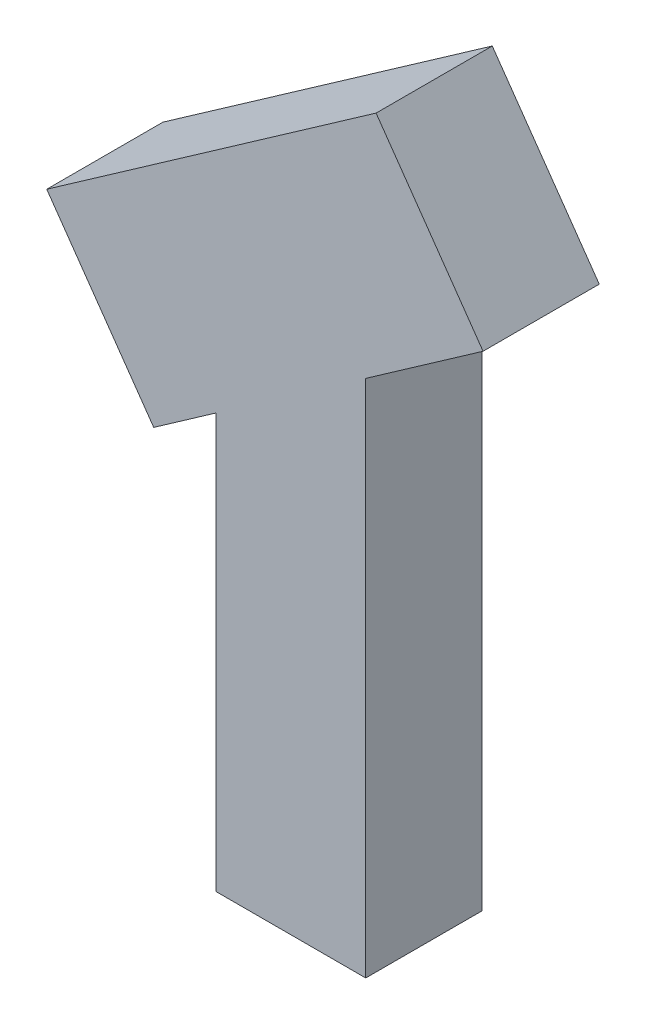
SolidWorks part; units mm, degrees
ref_plane "Alzado" through (0, 0, 0) normal (0, 0, 1) x (1, 0, 0)
ref_plane "Planta" through (0, 0, 0) normal (0, 1, 0) x (1, 0, 0)
ref_plane "Vista lateral" through (0, 0, 0) normal (1, 0, 0) x (0, 0, -1)
sketch "Croquis1" plane through (0, 0, 0) normal (0, 0, 1) x (1, 0, 0)
  line L0 (0, -183.0462) -> (0, 46.9383) construction
  line L1 (-66.0929, 94.3904) -> (41.8373, -59.7498) construction
  line L2 (-117.8781, -82.5391) -> (138.6718, 97.0991) construction
  line L3 (-1.0795, -361) -> (61.9205, -361)
  line L4 (-1.0795, -361) -> (-36.0795, -361)
  line L5 (61.9205, -361) -> (61.9205, -21.3133)
  line L6 (61.9205, -21.3133) -> (138.6718, 32.4286)
  line L7 (138.6718, 32.4286) -> (68.6955, 132.3652)
  line L8 (-36.0795, -89.9336) -> (-36.0795, -361)
  line L9 (68.6955, 132.3652) -> (-146.7415, -18.4854)
  line L10 (-146.7415, -18.4854) -> (-76.7652, -118.422)
  line L11 (-76.7652, -118.422) -> (-36.0795, -89.9336)
  point P14 (0, 0)
  point P18 (0, 0)
  dimension "D1" = 35
  dimension "D2" = 361
  dimension "D3" = 98
  dimension "D4" = 63
  dimension "D5" = 122
  dimension "D6" = 263
extrude "Saliente-Extruir1" add sketch "Croquis1" along normal mid plane 76
sketch "Croquis2" plane through (0, 0, 0) normal (0, 0, 1) x (1, 0, 0)
  line L0 (-101.0682, -26.1799) -> (-68.3744, -72.8715)
  line L1 (-68.3744, -72.8715) -> (92.9986, 40.123)
  line L2 (-101.0682, -26.1799) -> (60.3047, 86.8147)
  line L3 (60.3047, 86.8147) -> (92.9986, 40.123)
  line L4 (138.6718, 32.4286) -> (68.6955, 132.3652) construction
  line L5 (68.6955, 132.3652) -> (-146.7415, -18.4854) construction
  line L6 (-146.7415, -18.4854) -> (-76.7652, -118.422) construction
  dimension "D1" = 57
  dimension "D2" = 197
  dimension "D3" = 32.5
  dimension "D4" = 33
extrude "Cortar-Extruir4" cut sketch "Croquis2" against normal mid plane 22 from surface at -38 starting at face at (4.4428, -100.6701, -38)
